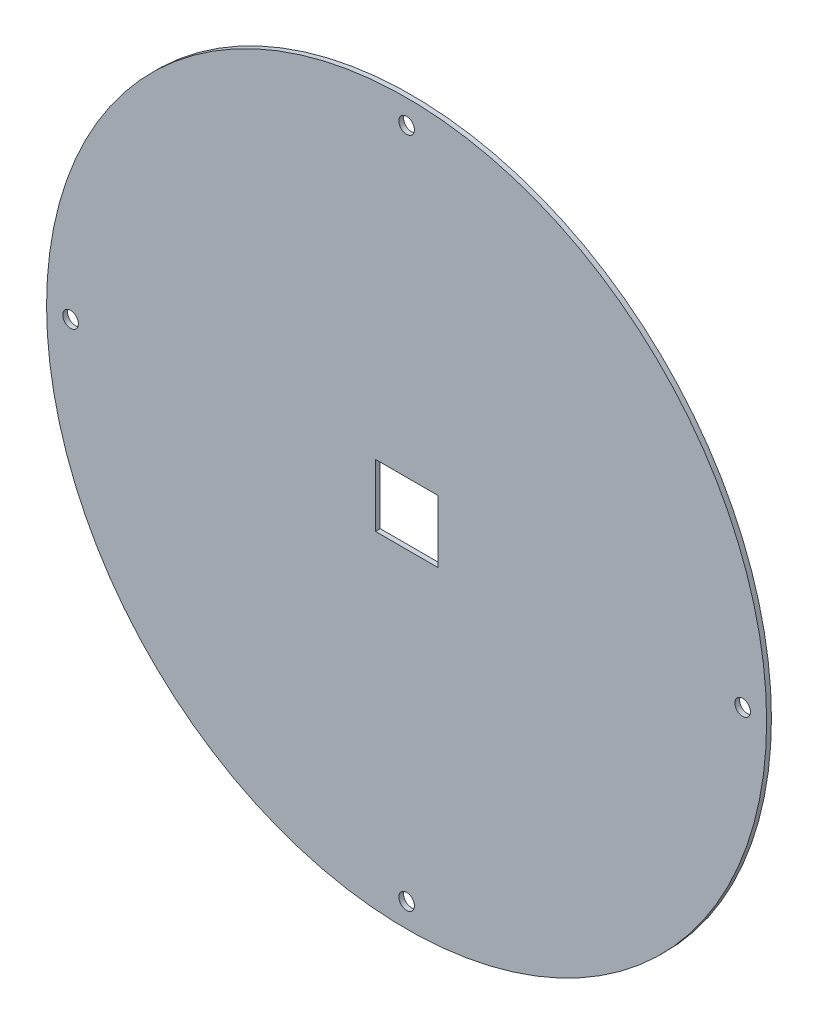
SolidWorks part; units mm, degrees
ref_plane "Alzado" through (0, 0, 0) normal (0, 0, 1) x (1, 0, 0)
ref_plane "Planta" through (0, 0, 0) normal (0, 1, 0) x (1, 0, 0)
ref_plane "Vista lateral" through (0, 0, 0) normal (1, 0, 0) x (0, 0, -1)
sketch "Croquis1" plane through (0, 0, 0) normal (0, 0, 1) x (1, 0, 0)
  line L0 (0, 0) -> (140, 0) construction
  circle A0 centre (0, 0) radius 150
  circle A1 centre (140, 0) radius 3.25
  circle A2 centre (0, -140) radius 3.25
  circle A3 centre (-140, 0) radius 3.25
  circle A4 centre (0, 140) radius 3.25
  dimension "D1" = 300
  dimension "D2" = 6.5
  dimension "D3" = 140
  dimension "D5" = 140
  dimension "D4" = 4
extrude "Saliente-Extruir1" add sketch "Croquis1" along normal blind 2
sketch "Croquis2" plane through (0, 0, 2) normal (0, 0, 1) x (1, 0, 0)
  line L1 (-13, 13) -> (13, 13)
  line L2 (-13, 13) -> (-13, -13)
  line L3 (-13, -13) -> (13, -13)
  line L4 (13, 13) -> (13, -13)
  point P4 (0, 13)
  point P6 (-13, 0)
  dimension "D1" = 26
extrude "Cortar-Extruir1" cut sketch "Croquis2" against normal through all
